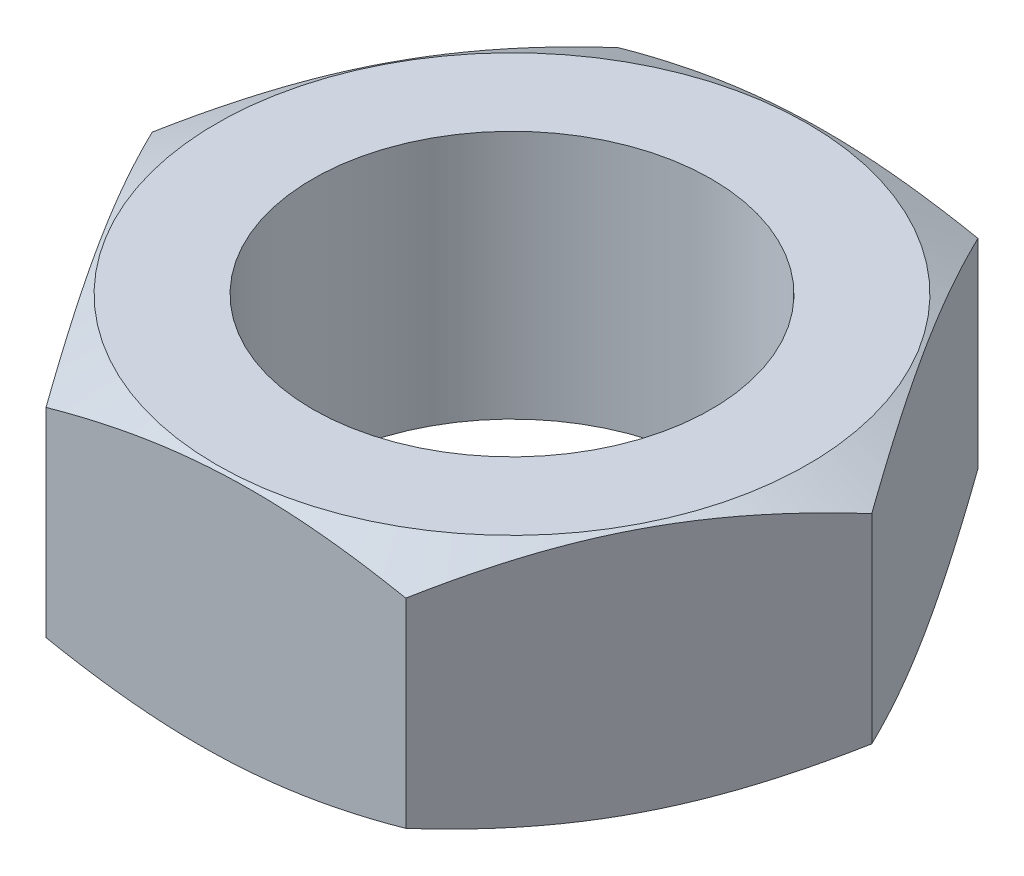
SolidWorks part; units mm, degrees
ref_plane "前视基准面" through (0, 0, 0) normal (0, 0, 1) x (1, 0, 0)
ref_plane "上视基准面" through (0, 0, 0) normal (0, 1, 0) x (1, 0, 0)
ref_plane "右视基准面" through (0, 0, 0) normal (1, 0, 0) x (0, 0, -1)
sketch "草图1" plane through (0, 0, 0) normal (0, 1, 0) x (1, 0, 0)
  line L1 (3.2059, 6.1418) -> (-3.716, 5.8473)
  line L2 (-3.716, 5.8473) -> (-6.9219, -0.2945)
  line L3 (-6.9219, -0.2945) -> (-3.2059, -6.1418)
  line L4 (-3.2059, -6.1418) -> (3.716, -5.8473)
  line L5 (3.716, -5.8473) -> (6.9219, 0.2945)
  line L6 (6.9219, 0.2945) -> (3.2059, 6.1418)
  circle A0 centre (0, 0) radius 6 construction
  circle A1 centre (0, 0) radius 4
  dimension "D1" = 12
  dimension "D2" = 8
extrude "凸台-拉伸1" add sketch "草图1" along normal blind 5
ref_plane "基准面1" through (0, 0, 0) normal (0.8865, 0, 0.4627) x (0.4627, 0, -0.8865)
sketch "草图2" plane through (0, 0, 0) normal (0.8865, 0, 0.4627) x (0.4627, 0, -0.8865)
  line L0 (-6.9282, 4.5) -> (-6.9282, 5)
  line L1 (-6.9282, 5) -> (-6.9282, 0) construction
  line L2 (-6.9282, 5) -> (-5.9282, 5)
  line L3 (-6.9282, 5) -> (-3.4641, 5) construction
  line L4 (-5.9282, 5) -> (-6.9282, 4.5)
  line L5 (-3003.4641, 2.5) -> (996.5359, 2.5) construction
  line L6 (-3.4641, 5) -> (-3.4641, 0) construction
  line L7 (-6.9282, 0.5) -> (-6.9282, 0)
  line L8 (-5.9282, 0) -> (-6.9282, 0.5)
  line L9 (-6.9282, 0) -> (-5.9282, 0)
  line L10 (0, 0) -> (0, 6.5432) construction
  point P14 (-3.4641, 2.5)
  point P15 (-1003.4641, 2.5)
  dimension "D1" = 1
  dimension "D2" = 0.5
revolve "切除-旋转1" cut sketch "草图2" angle 360 about L10
